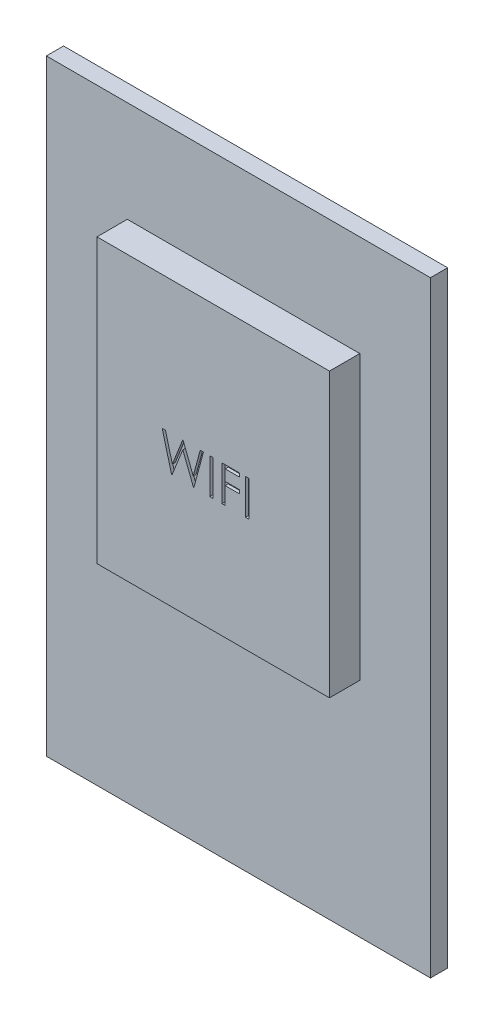
SolidWorks part; units mm, degrees
ref_plane "Front Plane" through (0, 0, 0) normal (0, 0, 1) x (1, 0, 0)
ref_plane "Top Plane" through (0, 0, 0) normal (0, 1, 0) x (1, 0, 0)
ref_plane "Right Plane" through (0, 0, 0) normal (1, 0, 0) x (0, 0, -1)
sketch "Sketch1" plane through (0, 0, 0) normal (0, 0, 1) x (1, 0, 0)
  line L1 (-19, 30) -> (19, 30)
  line L2 (-19, 30) -> (-19, -30)
  line L3 (-19, -30) -> (19, -30)
  line L4 (19, 30) -> (19, -30)
  point P4 (0, 30)
  point P5 (-19, 0)
  dimension "D1" = 38
  dimension "D2" = 60
extrude "Boss-Extrude1" add sketch "Sketch1" along normal blind 1.7
sketch "Sketch2" plane through (0, 0, 1.7) normal (0, 0, 1) x (1, 0, 0)
  line L0 (-19, 30) -> (-19, -30) construction
  line L1 (19, 30) -> (-19, 30) construction
  circle A0 centre (-13, 24) radius 2.05
  circle A1 centre (47, 24) radius 2.05
  circle A2 centre (47, -46) radius 2.05
  circle A3 centre (-13, -46) radius 2.05
  dimension "D3" = 4.1
  dimension "D1" = 6
  dimension "D2" = 6
  dimension "D4" = 2
  dimension "D5" = 2
extrude "Cut-Extrude1" [suppressed] cut sketch "Sketch2" against normal through all
sketch "Sketch3" plane through (0, 0, 1.7) normal (0, 0, 1) x (1, 0, 0)
  line L0 (19, 30) -> (-19, 30) construction
  line L1 (-10.9932, 20.0044) -> (12.0068, 20.0044)
  line L2 (-10.9932, 20.0044) -> (-10.9932, -7.9956)
  line L3 (-10.9932, -7.9956) -> (12.0068, -7.9956)
  line L4 (12.0068, 20.0044) -> (12.0068, -7.9956)
  point P6 (0.5068, 20.0044)
  dimension "D1" = 9.9956
  dimension "D2" = 28
  dimension "D3" = 23
extrude "Boss-Extrude2" add sketch "Sketch3" along normal blind 3
sketch "Sketch4" plane through (0, 0, 4.7) normal (0, 0, 1) x (1, 0, 0)
  line L0 (-10.9932, 20.0044) -> (-10.9932, -7.9956) construction
  line L1 (12.0068, 20.0044) -> (-10.9932, 20.0044) construction
  text T0 "WIFI"
  point P1 (-4.7678, 5.8256)
  point P6 (0, 0)
  dimension "D1" = 6.2255
  dimension "D2" = 16.6788
extrude "Cut-Extrude2" cut sketch "Sketch4" against normal blind 0.3
